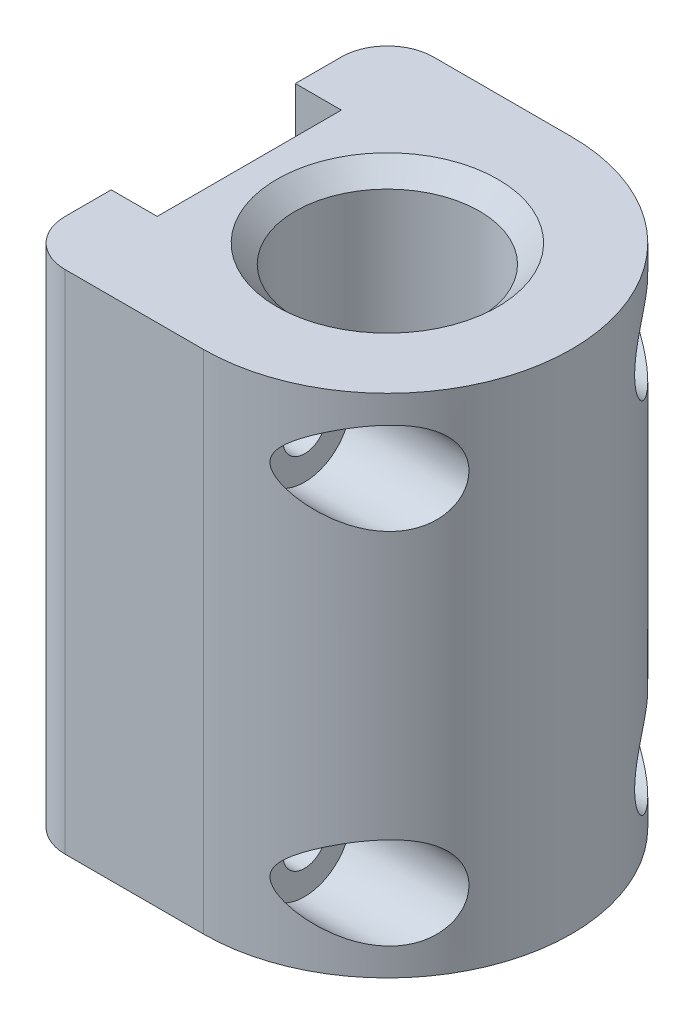
SolidWorks part; units mm, degrees
ref_plane "Front Plane" through (0, 0, 0) normal (0, 0, 1) x (1, 0, 0)
ref_plane "Top Plane" through (0, 0, 0) normal (0, 1, 0) x (1, 0, 0)
ref_plane "Right Plane" through (0, 0, 0) normal (1, 0, 0) x (0, 0, -1)
other "Configuration Table"
sketch "Sketch1" plane through (0, 0, 0) normal (0, 1, 0) x (1, 0, 0)
  line L1 (0, 5.08) -> (-5.08, 5.08)
  line L2 (0, 5.08) -> (0, -5.08)
  line L3 (0, -5.08) -> (-5.08, -5.08)
  line L4 (-5.08, 5.08) -> (-5.08, -5.08)
  line L5 (0, 5.08) -> (-5.08, -5.08) construction
  line L6 (0, -5.08) -> (-5.08, 5.08) construction
  line L7 (-5.08, 2.54) -> (-3.81, 2.54)
  line L8 (-5.08, 2.54) -> (-5.08, -2.54)
  line L9 (-5.08, -2.54) -> (-3.81, -2.54)
  line L10 (-3.81, 2.54) -> (-3.81, -2.54)
  line L11 (-5.08, 2.54) -> (-3.81, -2.54) construction
  line L12 (-5.08, -2.54) -> (-3.81, 2.54) construction
  circle A0 centre (0, 0) radius 5.08
  point P7 (-2.54, 0)
  point P12 (-4.445, 0)
  dimension "D1" = 10.16
  dimension "D2" = 5.08
  dimension "D3" = 5.08
  dimension "D4" = 1.27
extrude "Boss-Extrude1" add sketch "Sketch1" along normal blind 13.97 contours A0 L1 L4 | L2 A0 | A0 L4 L3 | L2 A0
sketch "Sketch2" plane through (0, 13.97, 0) normal (0, 1, 0) x (1, 0, 0)
  circle A0 centre (0, 0) radius 2.54
  dimension "D1" = 5.08
extrude "Cut-Extrude1" cut sketch "Sketch2" against normal blind 10.16
sketch "Sketch4" plane through (0, 0, 0) normal (1, 0, 0) x (0, 0, -1)
  line L0 (-3.556, 2.032) -> (3.556, 2.032) construction
  line L1 (-3.556, 2.032) -> (-3.556, 11.938) construction
  line L2 (-3.556, 11.938) -> (3.556, 11.938) construction
  line L3 (3.556, 11.938) -> (3.556, 2.032) construction
  line L4 (5.08, 13.97) -> (-5.08, 13.97) construction
  circle A0 centre (-3.556, 2.032) radius 1.27
  circle A1 centre (3.556, 2.032) radius 1.27
  circle A2 centre (-3.556, 11.938) radius 1.27
  circle A3 centre (3.556, 11.938) radius 1.27
  point P2 (0, 2.032)
  dimension "D1" = 2.032
  dimension "D3" = 2.54
  dimension "D2" = 7.112
  dimension "D4" = 2.032
extrude "Cut-Extrude3" cut sketch "Sketch4" against normal blind 5.08 from offset 6.35
fillet "Fillet2" radius 1.27 2 edges at (-5.08, 6.985, -5.08) (-5.08, 6.985, 5.08)
chamfer "Chamfer2" distance 0.508 angle 45 1 edges at (0, 13.97, 2.54)
scale "Scale1" scale about centroid uniform scaling yes scale factor 1.5
hole_wizard "#50 (0.07) Diameter Hole1" positions "Sketch9" profile "Sketch8" hole size "#50" standard "ANSI Inch" end condition through all
sketch "Sketch9" plane through (2.053, 0, 0) normal (1, 0, 0) x (0, 0, -1)
  circle A0 centre (-5.334, 14.6325) radius 1.905 construction
  circle A1 centre (5.334, 14.6325) radius 1.905 construction
  point P5 (-5.334, -0.2265)
  point P8 (5.334, -0.2265)
  point P11 (5.334, 14.6325)
  point P15 (-5.334, 14.6325)
sketch "Sketch8" plane through (2.053, -0.2265, 5.334) normal (0, 1, 0) x (0, 0, -1)
  line L0 (0, 0) -> (0, 9.525)
  line L1 (0, 9.525) -> (0.889, 9.525)
  line L2 (0.889, 9.525) -> (0.889, 0)
  line L5 (0.889, 0) -> (0, 0)
  line L11 (0, -6.35) -> (0, 107.95) construction
  dimension "Thru Hole Dia." = 1.778
  dimension "Thru Hole Depth" = 9.525
equation "\"0.0i9n\"=0.1"
